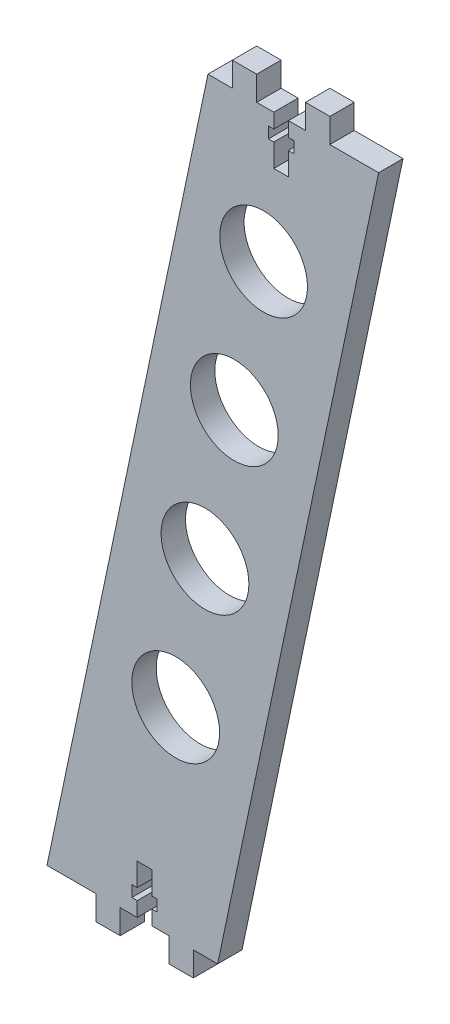
SolidWorks part; units mm, degrees
ref_plane "Plan de face" through (0, 0, 0) normal (0, 0, 1) x (1, 0, 0)
ref_plane "Plan de dessus" through (0, 0, 0) normal (0, 1, 0) x (1, 0, 0)
ref_plane "Plan de droite" through (0, 0, 0) normal (1, 0, 0) x (0, 0, -1)
sketch "Esquisse1" plane through (0, 0, 0) normal (0, 0, 1) x (1, 0, 0)
  line L0 (10, 0) -> (15, 0)
  line L1 (15, 0) -> (48, 157)
  line L2 (48, 157) -> (38, 157)
  line L3 (18, 157) -> (13, 157)
  line L4 (13, 157) -> (-20, 0)
  line L5 (-20, 0) -> (-10, 0)
  line B0 (-2.6, 3) -> (-2.6, 5.3)
  line B1 (1.5, 5.3) -> (1.5, 10)
  line B2 (-1.5, 10) -> (-1.5, 5.3)
  line B3 (-2.6, 5.3) -> (-1.5, 5.3)
  line B4 (0, 0) -> (0, 11.2208) construction
  line B5 (-1.5, 0) -> (-5, 0)
  line B6 (-5, -5) -> (-10, -5)
  line B7 (-10, -5) -> (-10, 0)
  line B8 (-5, -5) -> (-5, 0)
  line B9 (1.5, 0) -> (5, 0)
  line B10 (5, 0) -> (5, -5)
  line B11 (5, -5) -> (10, -5)
  line B12 (10, -5) -> (10, 0)
  line B13 (-1.5, 0) -> (1.5, 0) construction
  line B14 (1.5, 0) -> (1.5, 3)
  line B15 (1.5, 5.3) -> (2.6, 5.3)
  line B16 (2.6, 3) -> (1.5, 3)
  line B17 (1.5, 10) -> (-1.5, 10)
  line B18 (-1.5, 3) -> (-2.6, 3)
  line B19 (2.6, 5.3) -> (2.6, 3)
  line B20 (-1.5, 3) -> (-1.5, 0)
  line B21 (0, 10) -> (0, 0) construction
  line B22 (30.6, 154) -> (30.6, 151.7)
  line B23 (26.5, 151.7) -> (26.5, 147)
  line B24 (29.5, 147) -> (29.5, 151.7)
  line B25 (30.6, 151.7) -> (29.5, 151.7)
  line B26 (28, 157) -> (28, 145.7792) construction
  line B27 (29.5, 157) -> (33, 157)
  line B28 (33, 162) -> (38, 162)
  line B29 (38, 162) -> (38, 157)
  line B30 (33, 162) -> (33, 157)
  line B31 (26.5, 157) -> (23, 157)
  line B32 (23, 157) -> (23, 162)
  line B33 (23, 162) -> (18, 162)
  line B34 (18, 162) -> (18, 157)
  line B35 (29.5, 157) -> (26.5, 157) construction
  line B36 (26.5, 157) -> (26.5, 154)
  line B37 (26.5, 151.7) -> (25.4, 151.7)
  line B38 (25.4, 154) -> (26.5, 154)
  line B39 (26.5, 147) -> (29.5, 147)
  line B40 (29.5, 154) -> (30.6, 154)
  line B41 (25.4, 151.7) -> (25.4, 154)
  line B42 (29.5, 154) -> (29.5, 157)
  line B43 (28, 147) -> (28, 157) construction
  dimension "D1" = 10
  dimension "D2" = 5
  dimension "D3" = 28
  dimension "D4" = 157
sketch_block_instance "Insert M3 plots ep 5mm-1"
sketch_block "Insert M3 plots ep 5mm" parameters "D1"=10, "D2"=5, "D3"=5
sketch_block_instance "Decoupe Insert M3-4"
sketch_block "Decoupe Insert M3" parameters "D1"=5.2, "D2"=3, "D3"=2.3, "D4"=3, "D5"=10
sketch_block_instance "Insert M3 plots ep 5mm-2"
extrude "Boss.-Extru.1" add sketch "Esquisse1" along normal blind 5 contours B42 B40 B22 B25 B24 B39 B23 B37 B41 B38 B36 B31 B32 B33 B34 L3 L4 L5 B7 B6 B8 B5 B20 B18 B0 B3 B2 B17 B1 B15 B19 B16 B14 B9 B10 B11 B12 L0 L1 L2 B29 B28 B30 B27
sketch "Esquisse2" plane through (0, 0, 5) normal (0, 0, 1) x (1, 0, 0)
  line L0 (28, 147) -> (0, 10) construction
  line L1 (26.5, 147) -> (29.5, 147) construction
  line L2 (1.5, 10) -> (-1.5, 10) construction
  line L4 (24.4117, 129.4429) -> (12.3973, 70.6581) construction
  circle A0 centre (24.4117, 129.4429) radius 9
  circle A1 centre (18.4045, 100.0505) radius 9
  circle A2 centre (12.3973, 70.6581) radius 9
  circle A3 centre (6.3901, 41.2657) radius 9
  dimension "D4" = 18
  dimension "D2" = 30
  dimension "D3" = 17.92
  dimension "D1" = 4
extrude "Enlèv. mat.-Extru.1" cut sketch "Esquisse2" against normal through all
